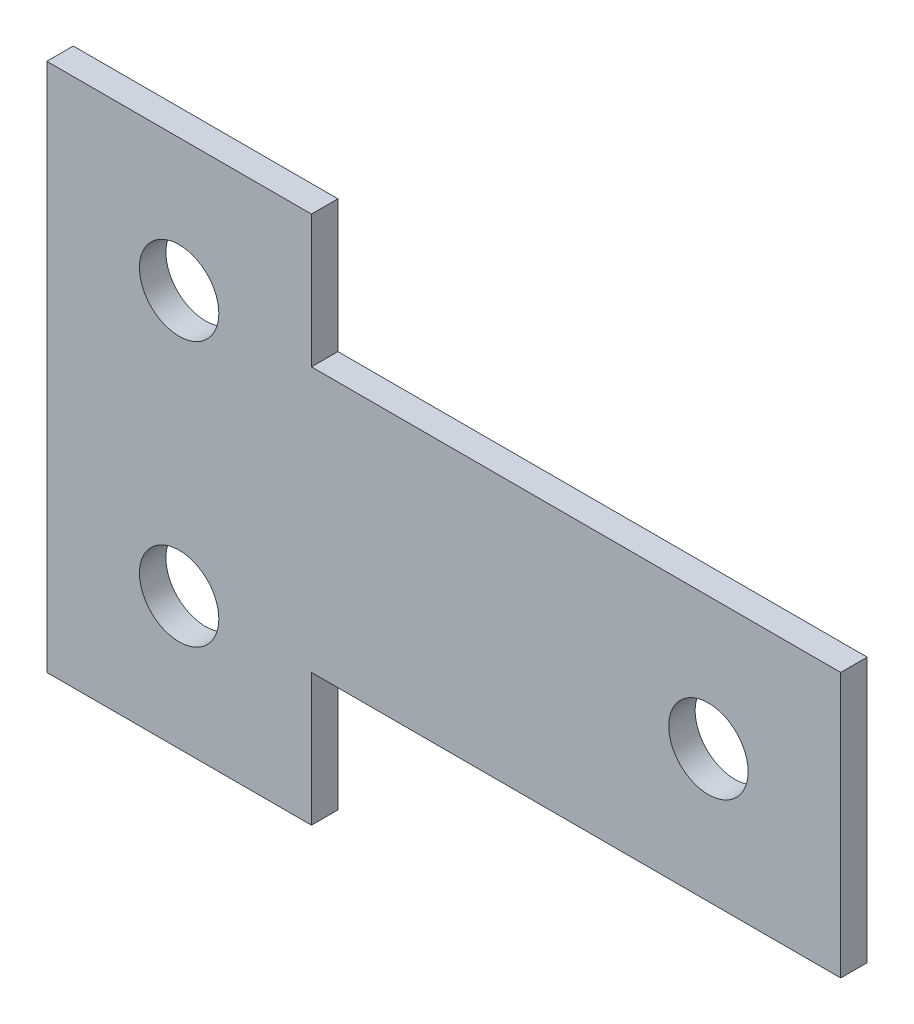
SolidWorks part; units mm, degrees
ref_plane "Płaszczyzna przednia" through (0, 0, 0) normal (0, 0, 1) x (1, 0, 0)
ref_plane "Płaszczyzna górna" through (0, 0, 0) normal (0, 1, 0) x (1, 0, 0)
ref_plane "Płaszczyzna prawa" through (0, 0, 0) normal (1, 0, 0) x (0, 0, -1)
sketch "Szkic1" plane through (0, 0, 0) normal (0, 0, 1) x (1, 0, 0)
  line L1 (-59.4355, 22.2) -> (-39.4355, 22.2)
  line L2 (-59.4355, 22.2) -> (-59.4355, -17.8)
  line L3 (-59.4355, -17.8) -> (-39.4355, -17.8)
  line L4 (-39.4355, 22.2) -> (-39.4355, -17.8)
  line L5 (-39.4355, 12.2) -> (0.5645, 12.2)
  line L6 (-39.4355, 12.2) -> (-39.4355, -7.8)
  line L7 (-39.4355, -7.8) -> (0.5645, -7.8)
  line L8 (0.5645, 12.2) -> (0.5645, -7.8)
  dimension "D1" = 20
  dimension "D2" = 40
  dimension "D3" = 20
  dimension "D4" = 10
  dimension "D5" = 40
extrude "Dodanie-wyciągnięcie1" add sketch "Szkic1" along normal blind 2 contours L8 L5 L4 L7 | L4 L1 L2 L3
sketch "Szkic2" plane through (0, 0, 2) normal (0, 0, 1) x (1, 0, 0)
  line L0 (-59.4355, 22.2) -> (-59.4355, -17.8) construction
  line L1 (-59.4355, 22.2) -> (-39.4355, 22.2) construction
  line L2 (-39.4355, 12.2) -> (0.5645, 12.2) construction
  line L3 (0.5645, 12.2) -> (0.5645, -7.8) construction
  circle A0 centre (-9.4355, 2.2) radius 3
  circle A1 centre (-49.4355, 12.2) radius 3
  circle A2 centre (-49.4355, -7.8) radius 3
  dimension "D1" = 6
  dimension "D2" = 6
  dimension "D3" = 6
  dimension "D6" = 20
  dimension "D7" = 10
  dimension "D4" = 10
  dimension "D5" = 10
  dimension "D8" = 10
  dimension "D9" = 10
extrude "Wytnij-wyciągnięcie1" cut sketch "Szkic2" against normal blind 2
